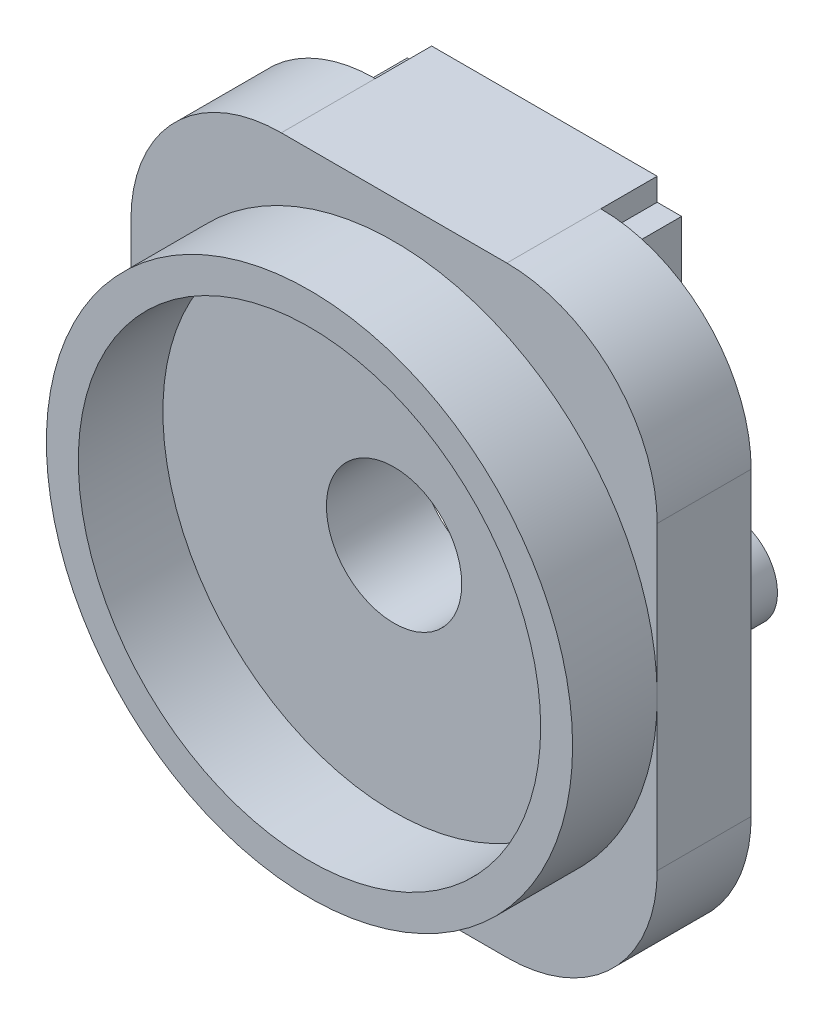
SolidWorks part; units mm, degrees
ref_plane "정면" through (0, 0, 0) normal (0, 0, 1) x (1, 0, 0)
ref_plane "윗면" through (0, 0, 0) normal (0, 1, 0) x (1, 0, 0)
ref_plane "우측면" through (0, 0, 0) normal (1, 0, 0) x (0, 0, -1)
sketch "스케치1" plane through (0, 0, 0) normal (0, 0, 1) x (1, 0, 0)
  line L1 (-6, 16) -> (6, 16)
  line L2 (-14, 8) -> (-14, -8)
  line L3 (-6, -16) -> (6, -16)
  line L4 (14, 8) -> (14, -8)
  line L6 (-14, 0) -> (14, 0) construction
  line L7 (0, 16) -> (0, -16) construction
  arc A0 (-6, -16) -> (-14, -8) centre (-6, -8) cw
  arc A1 (6, -16) -> (14, -8) centre (6, -8) ccw
  arc A2 (14, 8) -> (6, 16) centre (6, 8) ccw
  arc A3 (-6, 16) -> (-14, 8) centre (-6, 8) ccw
  dimension "D3" = 12
  dimension "D1" = 28
  dimension "D2" = 32
extrude "보스-돌출1" add sketch "스케치1" along normal blind 5 contours A3 L2 A0 L3 A1 L4 A2 L1
sketch "스케치2" plane through (0, 0, 5) normal (0, 0, 1) x (1, 0, 0)
  circle A0 centre (0, 0) radius 14
  circle A1 centre (0, 0) radius 12.3
  dimension "D1" = 28
  dimension "D2" = 24.6
extrude "보스-돌출2" add sketch "스케치2" along normal blind 4.5
sketch "스케치3" plane through (0, 0, 0) normal (0, 0, -1) x (-1, 0, 0)
  line L0 (7.15, 7.15) -> (-7.15, -7.15) construction
  line L1 (-7.9, 7.9) -> (-3.3, 7.9)
  line L2 (-7.9, 7.9) -> (-7.9, 2.4)
  line L3 (-7.9, -7.9) -> (7.9, -7.9)
  line L4 (7.9, 7.9) -> (7.9, 2.4)
  line L5 (-7.15, 7.15) -> (7.15, 7.15)
  line L6 (-7.15, 7.15) -> (-7.15, -7.15)
  line L7 (-7.15, -7.15) -> (7.15, -7.15)
  line L8 (7.15, 7.15) -> (7.15, -7.15)
  line L9 (-7.9, 7.9) -> (7.9, -7.9) construction
  line L10 (-10.7152, 0) -> (11.3029, 0) construction
  line L11 (0, 0) -> (0, 17.3363) construction
  line L12 (-10, 2.4) -> (-7.9, 2.4)
  line L13 (-10, -2.4) -> (-7.9, -2.4)
  line L14 (10, -2.4) -> (7.9, -2.4)
  line L15 (10, 2.4) -> (7.9, 2.4)
  line L16 (7.9, -2.4) -> (7.9, -7.9)
  line L17 (-7.9, -2.4) -> (-7.9, -7.9)
  line L18 (-6, 16) -> (6, 16)
  line L19 (6, 16) -> (-6, 16) construction
  line L20 (6, 16) -> (6, 14.8)
  line L21 (6, 14.8) -> (7.3, 14.8)
  line L22 (7.3, 14.8) -> (7.3, 9.8)
  line L23 (7.3, 9.8) -> (6, 9.8)
  line L24 (6, 9.8) -> (6, 8.6)
  line L25 (6, 8.6) -> (2.9, 8.6)
  line L26 (2.9, 8.6) -> (2.9, 7.9)
  line L27 (-6, 16) -> (-6, 14.8)
  line L28 (-6, 14.8) -> (-7.3, 14.8)
  line L29 (-7.3, 14.8) -> (-7.3, 9.8)
  line L30 (-7.3, 9.8) -> (-6, 9.8)
  line L31 (-6, 9.8) -> (-6, 8.6)
  line L32 (-6, 8.6) -> (-3.3, 8.6)
  line L33 (-3.3, 8.6) -> (-3.3, 7.9)
  line L34 (2.9, 7.9) -> (7.9, 7.9)
  arc A0 (10, -2.4) -> (10, 2.4) centre (10, 0) ccw
  arc A1 (-10, 2.4) -> (-10, -2.4) centre (-10, 0) ccw
  dimension "D6" = 4.8
  dimension "D1" = 15.8
  dimension "D2" = 15.8
  dimension "D3" = 14.3
  dimension "D4" = 14.3
  dimension "D5" = 20
  dimension "D7" = 12
  dimension "D8" = 1.2
  dimension "D9" = 5
  dimension "D10" = 14.6
  dimension "D11" = 5
  dimension "D12" = 4.6
  dimension "D13" = 1.2
extrude "보스-돌출3" add sketch "스케치3" along normal blind 3
sketch "스케치4" plane through (0, 0, 0) normal (0, 0, 1) x (1, 0, 0)
  circle A0 centre (0, 0) radius 3.6
  dimension "D1" = 7.2
extrude "컷-돌출2" cut sketch "스케치4" along normal through all
sketch "스케치5" plane through (0, 0, -3) normal (0, 0, -1) x (-1, 0, 0)
  point P0 (10, 0)
  point P1 (-10, 0)
hole_wizard "M2 여유 구멍1" positions "3D스케치1" profile "스케치6" hole size "M2" standard "Ansi Metric"
sketch3d "3D스케치1"
  point P0 (-10, 0, -3)
  point P3 (10, 0, -3)
sketch "스케치6" plane through (-10, 0, -3) normal (1, 0, 0) x (0, 1, 0)
  line L0 (0, 0) -> (0, 3.721)
  line L1 (0, 3.721) -> (1.2, 3)
  line L2 (1.2, 3) -> (1.2, 0)
  line L5 (1.2, 0) -> (0, 0)
  line L10 (0, 3.721) -> (-1.2, 3) construction
  line L11 (0, -6.35) -> (0, 107.95) construction
  dimension "구멍 지름" = 2.4
  dimension "구멍 깊이" = 3
  dimension "드릴 각도" = 118
